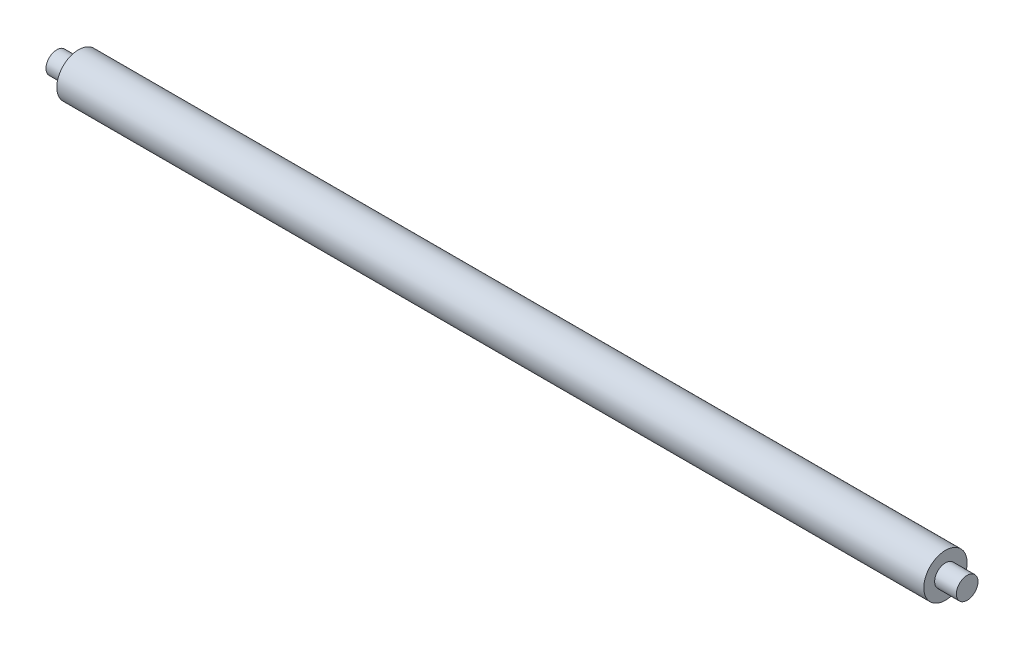
SolidWorks part; units mm, degrees
material "AISI Type 316L stainless steel"
ref_plane "Front Plane" through (0, 0, 0) normal (0, 0, 1) x (1, 0, 0)
ref_plane "Top Plane" through (0, 0, 0) normal (0, 1, 0) x (1, 0, 0)
ref_plane "Right Plane" through (0, 0, 0) normal (1, 0, 0) x (0, 0, -1)
sketch "Sketch1" plane through (0, 0, 0) normal (1, 0, 0) x (0, 0, -1)
  circle A0 centre (0, 0) radius 5
  dimension "D1" = 10
extrude "Boss-Extrude1" add sketch "Sketch1" along normal mid plane 200
sketch "Sketch2" plane through (100, 0, 0) normal (1, 0, 0) x (0, 0, -1)
  circle A0 centre (0, 0) radius 2.5
  dimension "D1" = 5
extrude "Boss-Extrude2" add sketch "Sketch2" along normal blind 5
mirror "Mirror1" about plane through (0, 0, 0) normal (1, 0, 0) of "Boss-Extrude2"
